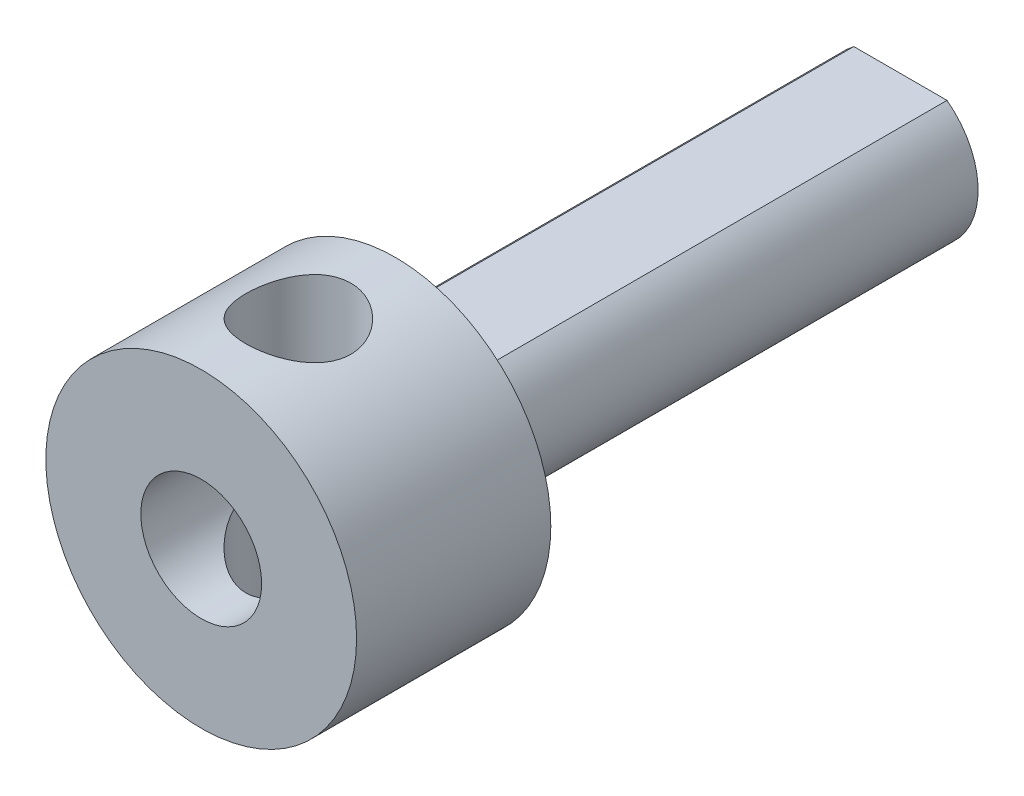
SolidWorks part; units mm, degrees
ref_plane "Front Plane" through (0, 0, 0) normal (0, 0, 1) x (1, 0, 0)
ref_plane "Top Plane" through (0, 0, 0) normal (0, 1, 0) x (1, 0, 0)
ref_plane "Right Plane" through (0, 0, 0) normal (1, 0, 0) x (0, 0, -1)
sketch "Sketch1" plane through (0, 0, 0) normal (0, 0, 1) x (1, 0, 0)
  circle A0 centre (0, 0) radius 4
  dimension "D1" = 8
extrude "Boss-Extrude1" add sketch "Sketch1" along normal blind 5
sketch "Sketch2" plane through (0, 0, 5) normal (0, 0, 1) x (1, 0, 0)
  circle A0 centre (0, 0) radius 1.555
  point P2 (0, 0)
  dimension "D1" = 3.11
sketch "Sketch3" plane through (0, 0, 0) normal (0, 0, -1) x (-1, 0, 0)
  line L0 (-1.2, 1.6) -> (1.2, 1.6)
  circle A0 centre (0, 0) radius 2
  dimension "D1" = 4
  dimension "D2" = 1.6
extrude "Cut-Extrude1" cut sketch "Sketch2" against normal blind 4
extrude "Boss-Extrude2" add sketch "Sketch3" along normal blind 13 contours L0 A0
ref_plane "Plane1" through (0, 4, 0) normal (0, 1, 0) x (1, 0, 0)
hole_wizard "#6-32 Tapped Hole2" positions "Sketch9" profile "Sketch10" tap size "#6-32" standard "ANSI Inch" end condition through all
sketch "Sketch9" plane through (0, 4, 0) normal (0, 1, 0) x (1, 0, 0)
  line L0 (4, 0) -> (-4, 0) construction
  point P0 (0, -2.5)
  point P6 (0, 0)
  dimension "D1" = 2.5
sketch "Sketch10" plane through (0, 4, 2.5) normal (1, 0, 0) x (0, 0, 1)
  line L0 (0, 0) -> (0, 8)
  line L1 (0, 8) -> (1.3525, 8)
  line L2 (1.3525, 8) -> (1.3525, 0)
  line L5 (1.3525, 0) -> (0, 0)
  line L11 (0, -6.35) -> (0, 107.95) construction
  dimension "Thru Tap Drill Dia." = 2.7051
  dimension "Thru Tap Drill Depth" = 8
cosmetic thread "Hole Thread2" parameters "D2"=3.5052
